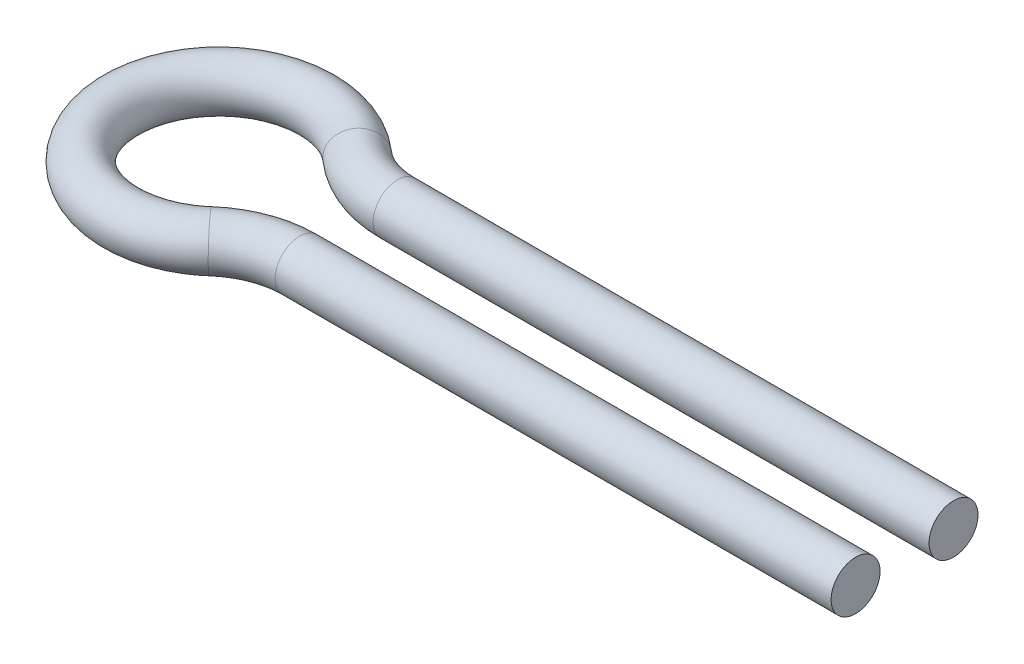
SolidWorks part; units mm, degrees
ref_plane "前视基准面" through (0, 0, 0) normal (0, 0, 1) x (1, 0, 0)
ref_plane "上视基准面" through (0, 0, 0) normal (0, 1, 0) x (1, 0, 0)
ref_plane "右视基准面" through (0, 0, 0) normal (1, 0, 0) x (0, 0, -1)
sketch "草图1" plane through (0, 0, 0) normal (0, 1, 0) x (1, 0, 0)
  line L0 (13.2288, 5) -> (70, 5)
  line L1 (0, 0) -> (102.1822, 0) construction
  line L2 (13.2288, -5) -> (70, -5)
  line L3 (70, 5) -> (70, -5) construction
  arc A0 (6.6144, 7.5) -> (6.6144, -7.5) centre (0, 0) ccw
  arc A1 (6.6144, 7.5) -> (13.2288, 5) centre (13.2288, 15) ccw
  arc A2 (6.6144, -7.5) -> (13.2288, -5) centre (13.2288, -15) cw
  dimension "D1" = 20
  dimension "D3" = 10
  dimension "D2" = 5
  dimension "D4" = 70
ref_plane "基准面1" through (70, 0, 0) normal (1, 0, 0) x (0, 0, -1)
sketch "草图3" plane through (70, 0, 0) normal (1, 0, 0) x (0, 0, -1)
  line L0 (10, 0) -> (-10, 0) construction
  circle A0 centre (5, 0) radius 2.5
  dimension "D1" = 5
  dimension "D2" = 5
sweep "扫描2" add profiles "草图3" path "草图1"
